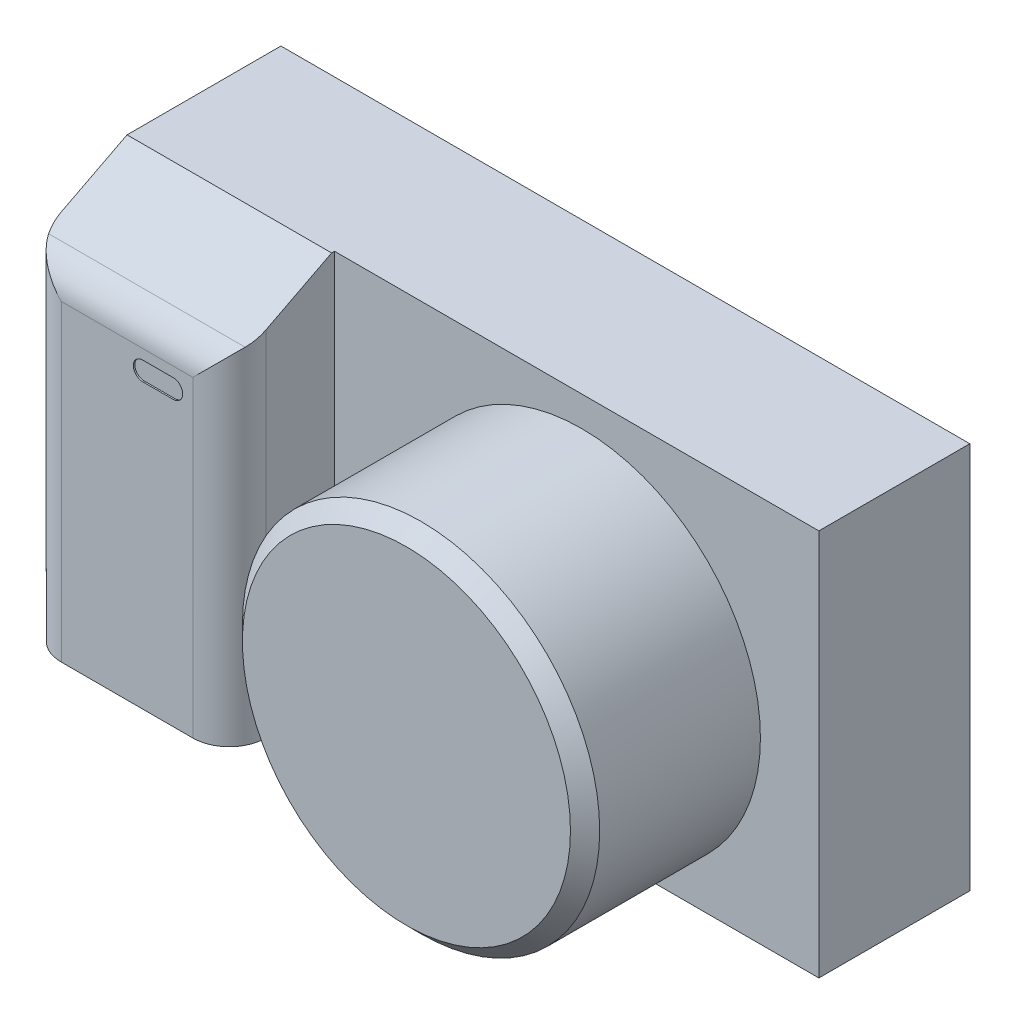
SolidWorks part; units mm, degrees
ref_plane "Front Plane" through (0, 0, 0) normal (0, 0, 1) x (1, 0, 0)
ref_plane "Top Plane" through (0, 0, 0) normal (0, 1, 0) x (1, 0, 0)
ref_plane "Right Plane" through (0, 0, 0) normal (1, 0, 0) x (0, 0, -1)
sketch "Sketch1" plane through (0, 0, 0) normal (0, 0, 1) x (1, 0, 0)
  line L1 (-59.8742, -33.655) -> (59.8741, -33.655)
  line L2 (-59.8742, -33.655) -> (-59.8742, 33.655)
  line L3 (-59.8742, 33.655) -> (59.8741, 33.655)
  line L4 (59.8741, -33.655) -> (59.8741, 33.655)
  line L5 (-59.8742, -33.655) -> (59.8741, 33.655) construction
  line L6 (-59.8742, 33.655) -> (59.8741, -33.655) construction
  point P0 (0, 0)
  dimension "D1" = 67.31
  dimension "D2" = 119.7483
extrude "Boss-Extrude1" add sketch "Sketch1" along normal blind 26.2382
sketch "Sketch2" plane through (0, 0, 26.2382) normal (0, 0, 1) x (1, 0, 0)
  line L0 (59.8741, -33.655) -> (59.8741, 33.655) construction
  line L1 (-59.8742, -33.655) -> (59.8741, -33.655) construction
  circle A0 centre (18.6626, -2.6035) radius 31.0515
  dimension "D1" = 62.103
  dimension "D2" = 41.2115
extrude "Boss-Extrude2" add sketch "Sketch2" along normal blind 30.48
chamfer "Chamfer1" distance 2.54 angle 45 1 edges at (49.7141, -2.6035, 56.7182)
sketch "Sketch3" plane through (0, 0, 26.2382) normal (0, 0, 1) x (1, 0, 0)
  line L0 (-59.8742, -33.655) -> (18.6626, -33.655) construction
  line L1 (-59.8742, 33.655) -> (-24.3142, 33.655)
  line L2 (-59.8742, 33.655) -> (-59.8742, -33.655)
  line L3 (-59.8742, -33.655) -> (-24.3142, -33.655)
  line L4 (-24.3142, 33.655) -> (-24.3142, -33.655)
  dimension "D1" = 35.56
extrude "Boss-Extrude3" add sketch "Sketch3" along normal blind 18.288
chamfer "Chamfer2" distance 17.78 distance2 9.144 1 edges at (-42.0942, 33.655, 44.5262)
fillet "Fillet1" radius 6.35 3 edges at (-42.0942, 24.511, 44.5262) (-24.3142, -4.572, 44.5262) (-59.8742, -4.572, 44.5262)
sketch "Sketch4" plane through (0, 0, 44.5262) normal (0, 0, 1) x (1, 0, 0)
  line L0 (-39.3637, 17.2569) -> (-34.063, 17.2569) construction
  line L1 (-39.3637, 18.8929) -> (-34.063, 18.8929)
  line L2 (-39.3637, 15.621) -> (-34.063, 15.621)
  line L3 (-53.5242, -33.655) -> (-30.6642, -33.655) construction
  line L4 (-59.8742, -33.655) -> (-59.8742, 27.7767) construction
  arc A0 (-39.3637, 18.8929) -> (-39.3637, 15.621) centre (-39.3637, 17.2569) ccw
  arc A1 (-34.063, 15.621) -> (-34.063, 18.8929) centre (-34.063, 17.2569) ccw
  point P2 (-36.7133, 17.2569)
  dimension "D3" = 49.276
  dimension "D4" = 20.5105
  dimension "D1" = 3.2719
  dimension "D2" = 5.3006
extrude "Cut-Extrude1" cut sketch "Sketch4" against normal blind 0.254 contours A1 L1 A0 L2
hole_wizard "1/4-20 Tapped Hole1" positions "Sketch6" profile "Sketch5" tap size "1/4-20" standard "ANSI Inch"
sketch "Sketch6" plane through (0, -33.655, 0) normal (0, -1, 0) x (-1, 0, 0)
  line L0 (-59.8741, -26.2382) -> (-59.8741, 0) construction
  line L1 (59.8742, 0) -> (-59.8741, 0) construction
  point P0 (-19.7421, -13.462)
  dimension "D1" = 40.132
  dimension "D2" = 13.462
sketch "Sketch5" plane through (19.7421, -33.655, 13.462) normal (1, 0, 0) x (0, 0, -1)
  line L0 (0, 0) -> (0, 18.0438)
  line L1 (0, 18.0438) -> (2.5527, 16.51)
  line L2 (2.5527, 16.51) -> (2.5527, 0)
  line L5 (2.5527, 0) -> (0, 0)
  line L10 (0, 18.0438) -> (-2.5527, 16.51) construction
  line L11 (0, -6.35) -> (0, 107.95) construction
  dimension "Tap Drill Dia." = 5.1054
  dimension "Tap Drill Depth" = 16.51
  dimension "Drill Angle" = 118
cosmetic thread "Hole Thread1" parameters "D1"=12.7, "D2"=6.35
equation "\"D2@Sketch2\"=\"D1@Sketch2\"/2+0.4"
equation "\"in\"=1.2"
equation "\"D1@Boss-Extrude3\"=1.75-1.03"
